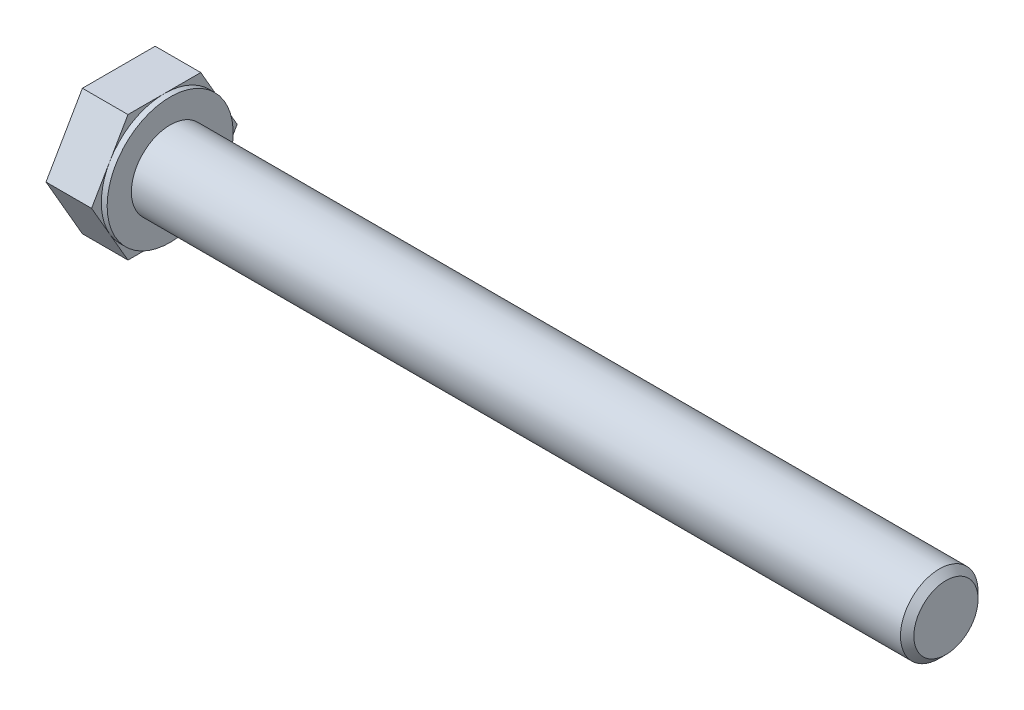
SolidWorks part; units mm, degrees
material "Alloy Steel"
ref_plane "Front Plane" through (0, 0, 0) normal (0, 0, 1) x (1, 0, 0)
ref_plane "Top Plane" through (0, 0, 0) normal (0, 1, 0) x (1, 0, 0)
ref_plane "Right Plane" through (0, 0, 0) normal (1, 0, 0) x (0, 0, -1)
sketch "BodySketch" plane through (0, 0, 0) normal (0, 1, 0) x (1, 0, 0)
  line L0 (0, 0) -> (80, 0) construction
  line L1 (79.3095, 4) -> (80, 3.3095)
  line L2 (0, 4) -> (0, 6.5)
  line L3 (0, 4) -> (79.3095, 4)
  line L4 (80, 0) -> (80, 3.3095)
  line L5 (0, 6.5) -> (-0.6, 6.5)
  line L6 (-0.6, 6.5) -> (-0.6, 0)
  line L7 (-0.6, 0) -> (80, 0)
  dimension "Diameter" = 8
  dimension "Body_ch_ang" = 45
  dimension "Width_flats" = 13
  dimension "Bearing_ht" = 0.6
  dimension "Length" = 80
revolve "BaseBody" add sketch "BodySketch" angle 360 about L0
cosmetic thread "Thread" parameters "Thread_length"=22, "Minor_dia"=6.619
sketch "HeadSketch" plane through (-0.6, 0, 0) normal (-1, 0, 0) x (0, 0, 1)
  line L1 (7.5056, 0) -> (3.7528, 6.5)
  line L2 (3.7528, 6.5) -> (-3.7528, 6.5)
  line L3 (-3.7528, 6.5) -> (-7.5056, 0)
  line L4 (-7.5056, 0) -> (-3.7528, -6.5)
  line L5 (-3.7528, -6.5) -> (3.7528, -6.5)
  line L6 (3.7528, -6.5) -> (7.5056, 0)
  circle A0 centre (0, 0) radius 6.5 construction
  circle A1 centre (0, 0) radius 6.5 construction
extrude "Hex" add sketch "HeadSketch" along normal blind 4.7
other "Freeze***"
other "PropertyManager"
